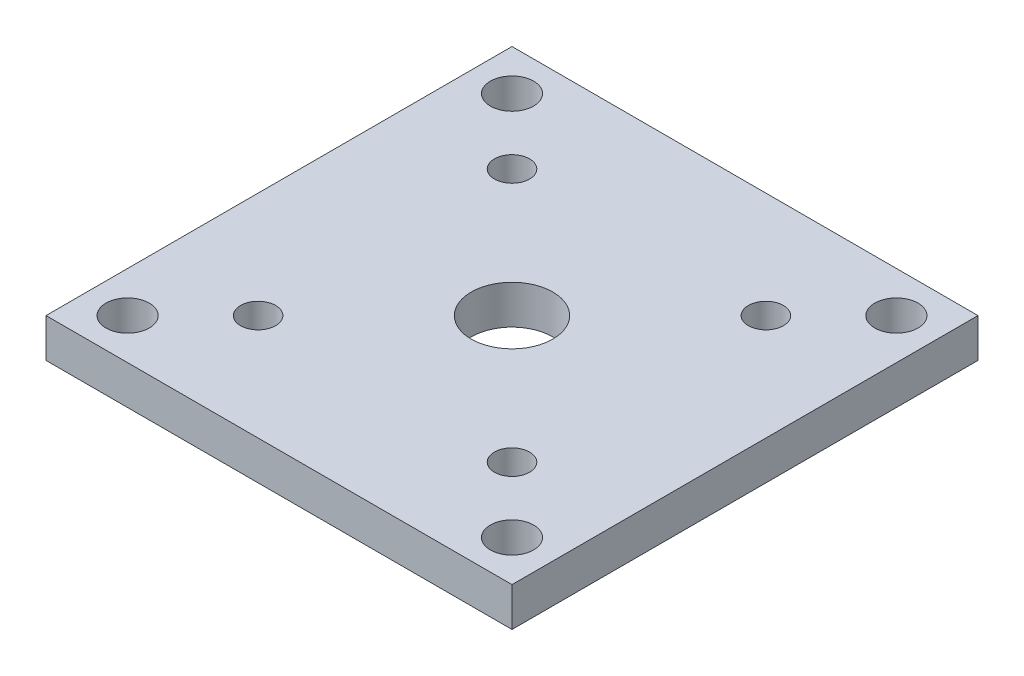
SolidWorks part; units mm, degrees
ref_plane "Front Plane" through (0, 0, 0) normal (0, 0, 1) x (1, 0, 0)
ref_plane "Top Plane" through (0, 0, 0) normal (0, 1, 0) x (1, 0, 0)
ref_plane "Right Plane" through (0, 0, 0) normal (1, 0, 0) x (0, 0, -1)
sketch "Sketch1" plane through (0, 0, 0) normal (0, 1, 0) x (1, 0, 0)
  line L0 (0, 57.1) -> (5, 52.1) construction
  line L1 (0, 0) -> (57.1, 0)
  line L2 (0, 0) -> (0, 57.1)
  line L3 (0, 57.1) -> (57.1, 57.1)
  line L4 (57.1, 0) -> (57.1, 57.1)
  line L5 (5, 52.1) -> (52.1, 52.1) construction
  line L6 (5, 52.1) -> (5, 5) construction
  line L7 (5, 5) -> (52.1, 5) construction
  line L8 (52.1, 52.1) -> (52.1, 5) construction
  line L9 (12.9937, 44.1063) -> (44.1063, 44.1063) construction
  line L10 (12.9937, 44.1063) -> (12.9937, 12.9937) construction
  line L11 (12.9937, 12.9937) -> (44.1063, 12.9937) construction
  line L12 (44.1063, 44.1063) -> (44.1063, 12.9937) construction
  line L13 (12.9937, 44.1063) -> (5, 52.1) construction
  line L14 (44.1063, 12.9937) -> (52.1, 5) construction
  line L15 (52.1, 5) -> (57.1, 0) construction
  line L16 (12.9937, 44.1063) -> (44.1063, 12.9937) construction
  circle A0 centre (12.9937, 44.1063) radius 2.15
  circle A1 centre (12.9937, 12.9937) radius 2.15
  circle A2 centre (44.1063, 12.9937) radius 2.15
  circle A3 centre (44.1063, 44.1063) radius 2.15
  circle A4 centre (5, 52.1) radius 2.65
  circle A5 centre (52.1, 52.1) radius 2.65
  circle A6 centre (52.1, 5) radius 2.65
  circle A7 centre (5, 5) radius 2.65
  circle A8 centre (28.55, 28.55) radius 5
  circle A9 centre (28.55, 28.55) radius 26.5 construction
  dimension "D2" = 47.1
  dimension "D3" = 4.3
  dimension "D4" = 5.3
  dimension "D5" = 10
  dimension "D7" = 53
  dimension "D1" = 44
  dimension "D6" = 5
extrude "Boss-Extrude1" add sketch "Sketch1" along normal blind 4.7625
